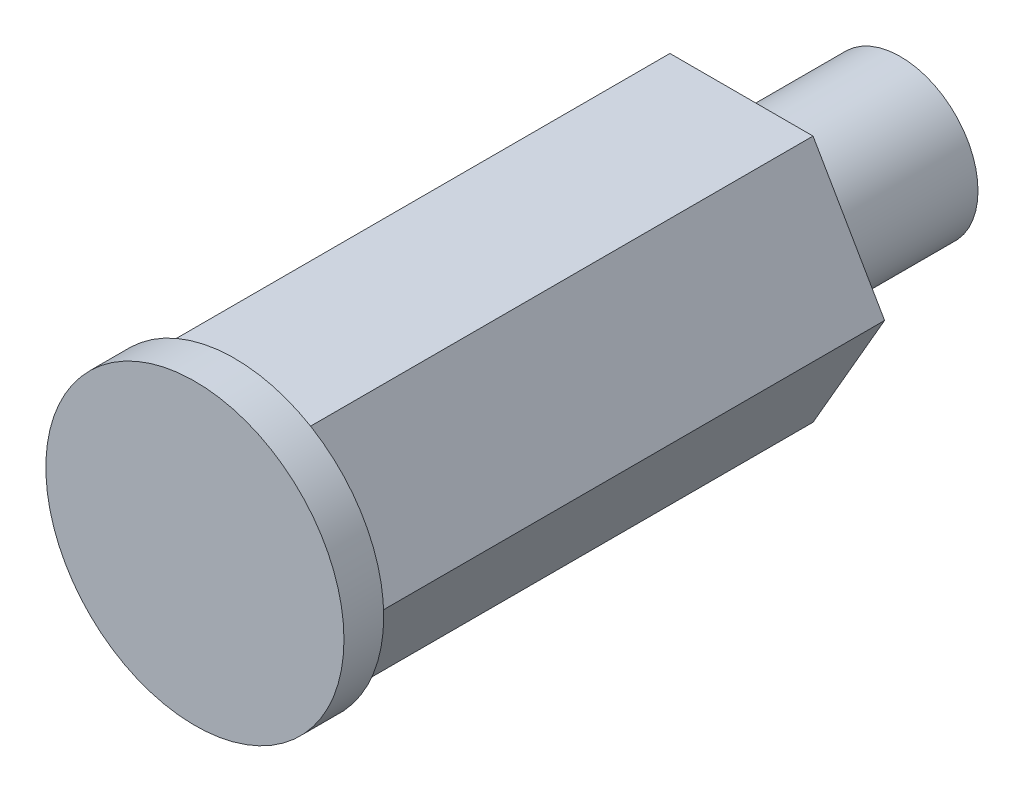
SolidWorks part; units mm, degrees
ref_plane "Front Plane" through (0, 0, 0) normal (0, 0, 1) x (1, 0, 0)
ref_plane "Top Plane" through (0, 0, 0) normal (0, 1, 0) x (1, 0, 0)
ref_plane "Right Plane" through (0, 0, 0) normal (1, 0, 0) x (0, 0, -1)
sketch "Sketch1" plane through (0, 0, 0) normal (0, 0, 1) x (1, 0, 0)
  line L0 (-2.0808, -2.02) -> (-2.0808, 2.02)
  line L1 (-2.0808, -2.02) -> (2.0808, -2.02) construction
  line L2 (-2.0808, -2.02) -> (-2.0808, 2.02) construction
  line L3 (-2.0808, 2.02) -> (2.0808, 2.02) construction
  line L4 (2.0808, -2.02) -> (2.0808, 2.02) construction
  line L5 (-2.0808, -2.02) -> (2.0808, 2.02) construction
  line L6 (-2.0808, 2.02) -> (2.0808, -2.02) construction
  line L7 (2.0808, -2.02) -> (2.0808, 2.02)
  circle A0 centre (0, 0) radius 2.9 construction
  arc A1 (-2.0808, 2.02) -> (2.0808, 2.02) centre (0, 0) cw
  arc A2 (-2.0808, -2.02) -> (2.0808, -2.02) centre (0, 0) ccw
  circle A3 centre (0, 0) radius 3.9
  dimension "D1" = 5.8
  dimension "D3" = 7.8
  dimension "D2" = 4.04
extrude "Boss-Extrude1" add sketch "Sketch1" along normal blind 8
sketch "Sketch2" plane through (0, 0, 8) normal (0, 0, 1) x (1, 0, 0)
  line L7 (3.6, 6.2354) -> (-3.6, 6.2354)
  line L8 (-3.6, 6.2354) -> (-7.2, 0)
  line L9 (-7.2, 0) -> (-3.6, -6.2354)
  line L10 (-3.6, -6.2354) -> (3.6, -6.2354)
  line L11 (3.6, -6.2354) -> (7.2, 0)
  line L12 (7.2, 0) -> (3.6, 6.2354)
  circle A0 centre (0, 0) radius 6.2354 construction
  point P1 (0, 6.2354)
  dimension "D1" = 7.2
extrude "Boss-Extrude2" add sketch "Sketch2" along normal blind 25.5 contours L7 L8 L9 L10 L11 L12
sketch "Sketch3" plane through (0, 0, 33.5) normal (0, 0, 1) x (1, 0, 0)
  circle A0 centre (0, 0) radius 7.5
  dimension "D1" = 15
extrude "Boss-Extrude3" add sketch "Sketch3" along normal blind 2
